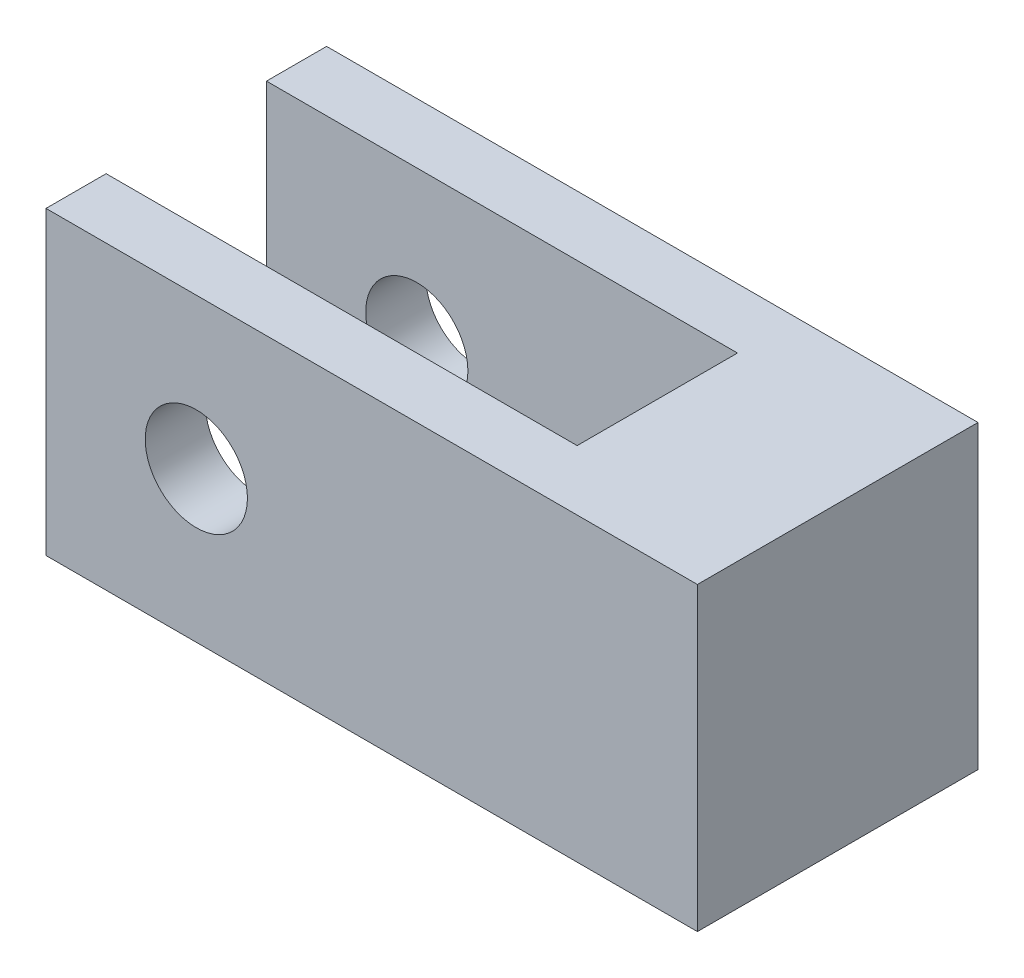
SolidWorks part; units mm, degrees
ref_plane "Front Plane" through (0, 0, 0) normal (0, 0, 1) x (1, 0, 0)
ref_plane "Top Plane" through (0, 0, 0) normal (0, 1, 0) x (1, 0, 0)
ref_plane "Right Plane" through (0, 0, 0) normal (1, 0, 0) x (0, 0, -1)
sketch "Sketch1" plane through (0, 0, 0) normal (0, 0, 1) x (1, 0, 0)
  line L1 (-15, 15) -> (50, 15)
  line L2 (-15, 15) -> (-15, -15)
  line L3 (-15, -15) -> (50, -15)
  line L4 (50, 15) -> (50, -15)
  dimension "D1" = 15
  dimension "D2" = 50
  dimension "D3" = 15
  dimension "D4" = 15
extrude "Boss-Extrude1" add sketch "Sketch1" along normal mid plane 28
sketch "Sketch2" plane through (0, 0, 0) normal (0, 0, 1) x (1, 0, 0)
  line L1 (-16, 16) -> (32, 16)
  line L2 (-16, 16) -> (-16, -16)
  line L3 (-16, -16) -> (32, -16)
  line L4 (32, 16) -> (32, -16)
  dimension "D1" = 16
  dimension "D2" = 32
  dimension "D3" = 16
  dimension "D4" = 16
extrude "Cut-Extrude1" cut sketch "Sketch2" against normal mid plane 16
sketch "Sketch3" plane through (0, 0, 0) normal (0, 0, 1) x (1, 0, 0)
  circle A0 centre (0, 0) radius 5.1
  dimension "D1" = 10.2
extrude "Cut-Extrude2" cut sketch "Sketch3" against normal through all both and the other way through all
